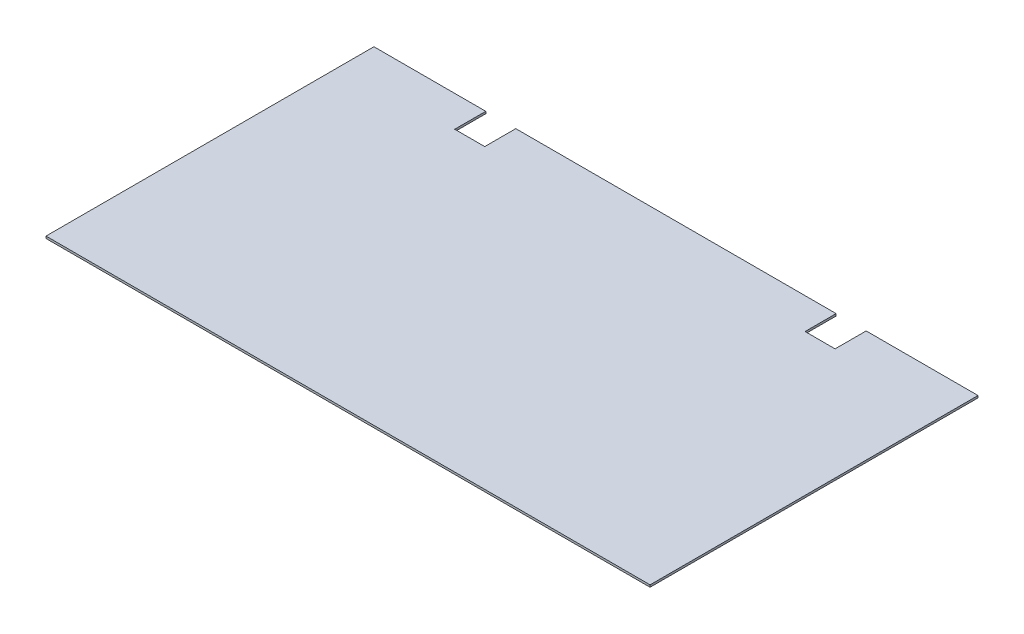
SolidWorks part; units mm, degrees
ref_plane "Front Plane" through (0, 0, 0) normal (0, 0, 1) x (1, 0, 0)
ref_plane "Top Plane" through (0, 0, 0) normal (0, 1, 0) x (1, 0, 0)
ref_plane "Right Plane" through (0, 0, 0) normal (1, 0, 0) x (0, 0, -1)
sketch "Sketch1" plane through (0, 0, 0) normal (0, 1, 0) x (1, 0, 0)
  line L1 (222.25, -120.65) -> (-222.25, -120.65)
  line L2 (222.25, -120.65) -> (222.25, 120.65)
  line L3 (222.25, 120.65) -> (-222.25, 120.65)
  line L4 (-222.25, -120.65) -> (-222.25, 120.65)
  line L5 (222.25, -120.65) -> (-222.25, 120.65) construction
  line L6 (222.25, 120.65) -> (-222.25, -120.65) construction
  point P0 (0, 0)
  dimension "D1" = 241.3
  dimension "D2" = 444.5
extrude "Boss-Extrude1" add sketch "Sketch1" along normal blind 1.5621
sketch "Sketch2" plane through (0, 1.5621, 0) normal (0, 1, 0) x (1, 0, 0)
  line L0 (222.25, 120.65) -> (-222.25, 120.65) construction
  line L1 (-139.954, 120.65) -> (-117.856, 120.65)
  line L2 (-139.954, 120.65) -> (-139.954, 97.79)
  line L3 (-139.954, 97.79) -> (-117.856, 97.79)
  line L4 (-117.856, 120.65) -> (-117.856, 97.79)
  line L5 (-222.25, 120.65) -> (-222.25, -120.65) construction
  line L6 (0, -0.8592) -> (0, 0.8592) construction
  line L7 (139.954, 97.79) -> (117.856, 97.79)
  line L8 (117.856, 120.65) -> (117.856, 97.79)
  line L9 (139.954, 120.65) -> (117.856, 120.65)
  line L10 (139.954, 120.65) -> (139.954, 97.79)
  dimension "D1" = 22.86
  dimension "D2" = 22.098
  dimension "D3" = 82.296
extrude "Cut-Extrude1" cut sketch "Sketch2" against normal up to next
